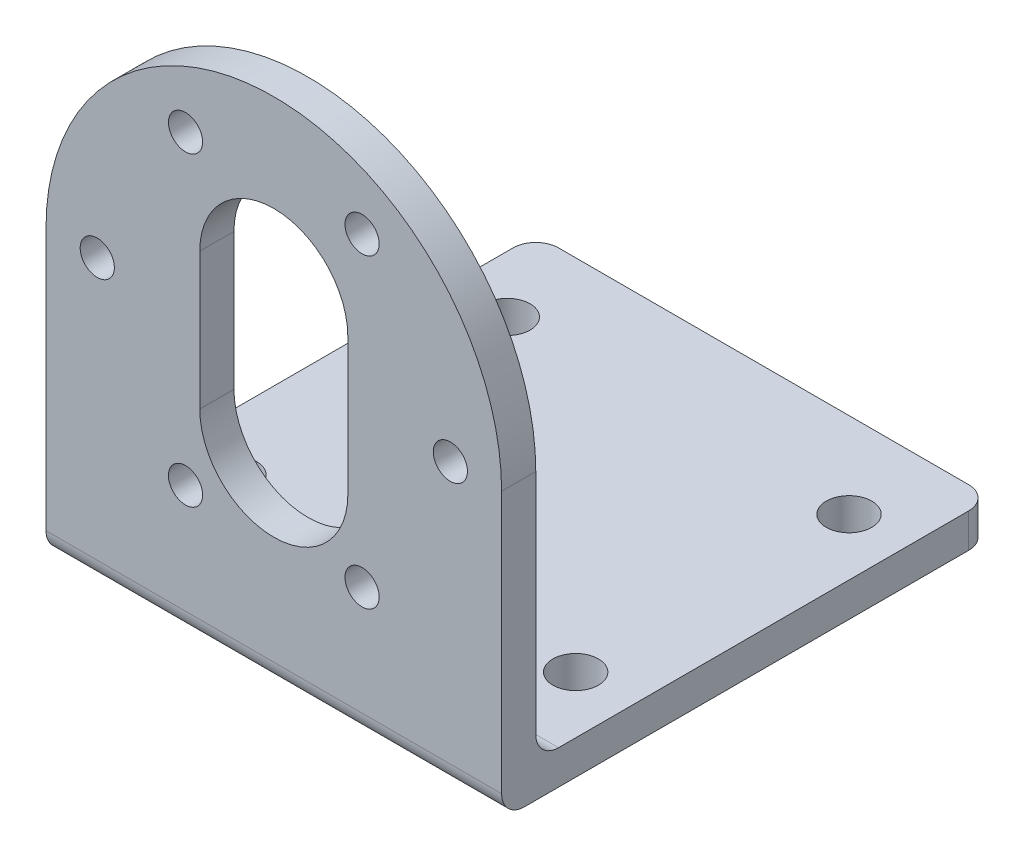
SolidWorks part; units mm, degrees
ref_plane "前视基准面" through (0, 0, 0) normal (0, 0, 1) x (1, 0, 0)
ref_plane "上视基准面" through (0, 0, 0) normal (0, 1, 0) x (1, 0, 0)
ref_plane "右视基准面" through (0, 0, 0) normal (1, 0, 0) x (0, 0, -1)
sketch "草图1" plane through (0, 0, 0) normal (0, 0, 1) x (1, 0, 0)
  line L0 (0, 0) -> (0, 29.7119) construction
  line L1 (7.75, 13.4234) -> (0, 0) construction
  line L2 (-20, 0) -> (-20, -25)
  line L3 (-20, -25) -> (20, -25)
  line L4 (20, -25) -> (20, 0)
  line L5 (0, 5) -> (0, -7) construction
  line L6 (6.5, 5) -> (6.5, -7)
  line L7 (-6.5, 5) -> (-6.5, -7)
  circle A0 centre (0, 0) radius 15.5 construction
  arc A1 (20, 0) -> (-20, 0) centre (0, 0) ccw
  circle A2 centre (7.75, 13.4234) radius 1.5
  circle A3 centre (15.5, 0) radius 1.5
  circle A4 centre (7.75, -13.4234) radius 1.5
  circle A5 centre (-7.75, -13.4234) radius 1.5
  circle A6 centre (-15.5, 0) radius 1.5
  circle A7 centre (-7.75, 13.4234) radius 1.5
  arc A8 (6.5, 5) -> (-6.5, 5) centre (0, 5) ccw
  arc A9 (-6.5, -7) -> (6.5, -7) centre (0, -7) ccw
  point P6 (0, -1)
  point P20 (0, 0)
  dimension "D1" = 31
  dimension "D2" = 40
  dimension "D3" = 3
  dimension "D8" = 7
  dimension "D9" = 5
  dimension "D4" = 30
  dimension "D6" = 25
  dimension "D7" = 13
  dimension "D5" = 6
extrude "凸台-拉伸1" add sketch "草图1" along normal blind 3
sketch "草图2" plane through (0, -25, 0) normal (0, -1, 0) x (1, 0, 0)
  line L0 (0, 0) -> (0, -64.2167) construction
  line L1 (20, 0) -> (-20, 0)
  line L2 (20, 0) -> (20, -38)
  line L3 (18, -40) -> (-18, -40)
  line L4 (-20, 0) -> (-20, -38)
  line L5 (-17.0218, -20.5) -> (11.7928, -20.5) construction
  circle A0 centre (-15, -32.5) radius 2
  circle A1 centre (-15, -8.5) radius 2
  circle A2 centre (15, -32.5) radius 2
  circle A3 centre (15, -8.5) radius 2
  arc A4 (18, -40) -> (20, -38) centre (18, -38) ccw
  arc A5 (-18, -40) -> (-20, -38) centre (-18, -38) cw
  point P22 (-20, -40)
  dimension "D2" = 4
  dimension "D6" = 2
  dimension "D1" = 40
  dimension "D3" = 24
  dimension "D4" = 7.5
  dimension "D5" = 30
extrude "凸台-拉伸2" add sketch "草图2" against normal blind 3
fillet "圆角1" radius 2 2 edges at (0, -22, 0) (0, -25, 3)
